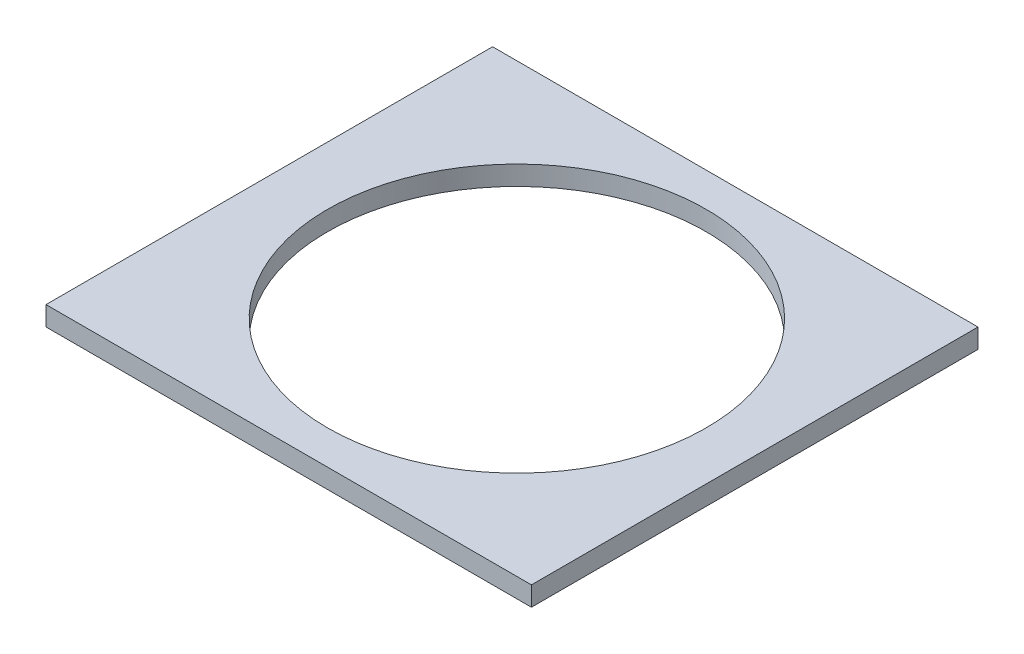
SolidWorks part; units mm, degrees
ref_plane "정면" through (0, 0, 0) normal (0, 0, 1) x (1, 0, 0)
ref_plane "윗면" through (0, 0, 0) normal (0, 1, 0) x (1, 0, 0)
ref_plane "우측면" through (0, 0, 0) normal (1, 0, 0) x (0, 0, -1)
sketch "스케치1" plane through (0, 0, 0) normal (0, 1, 0) x (1, 0, 0)
  line L1 (12.5, -11.5) -> (-12.5, -11.5)
  line L2 (12.5, -11.5) -> (12.5, 11.5)
  line L3 (12.5, 11.5) -> (-12.5, 11.5)
  line L4 (-12.5, -11.5) -> (-12.5, 11.5)
  line L5 (12.5, -11.5) -> (-12.5, 11.5) construction
  line L6 (12.5, 11.5) -> (-12.5, -11.5) construction
  point P0 (0, 0)
  dimension "D1" = 25
  dimension "D2" = 23
extrude "보스-돌출1" add sketch "스케치1" along normal blind 12
sketch "스케치2" plane through (0, 0, 0) normal (0, 1, 0) x (1, 0, 0)
  line L0 (12.5, 11.5) -> (-12.5, 11.5) construction
  line L1 (-11.5, 10.5) -> (13.5, 10.5)
  line L2 (-11.5, 10.5) -> (-11.5, -10.5)
  line L3 (-11.5, -10.5) -> (13.5, -10.5)
  line L4 (13.5, 10.5) -> (13.5, -10.5)
  line L5 (-12.5, 11.5) -> (-12.5, -11.5) construction
  dimension "D1" = 1
  dimension "D2" = 21
  dimension "D3" = 25
  dimension "D4" = 1
extrude "컷-돌출1" cut sketch "스케치2" along normal blind 11 from offset 1
sketch "스케치6" plane through (0, 0, 0) normal (0, 1, 0) x (1, 0, 0)
  line L1 (12.5, -11.5) -> (-12.5, -11.5)
  line L2 (12.5, -11.5) -> (12.5, 11.5)
  line L3 (12.5, 11.5) -> (-12.5, 11.5)
  line L4 (-12.5, -11.5) -> (-12.5, 11.5)
  line L5 (12.5, -11.5) -> (-12.5, 11.5) construction
  line L6 (12.5, 11.5) -> (-12.5, -11.5) construction
  point P0 (0, 0)
extrude "보스-돌출3" add sketch "스케치6" along normal blind 1 from offset 12 separate body
sketch "스케치8" plane through (0, 0, 0) normal (0, 1, 0) x (1, 0, 0)
  line L0 (-12.5, 11.5) -> (-12.5, -11.5) construction
  line L2 (-12.5, -11.5) -> (12.5, -11.5) construction
  circle A0 centre (0.25, 0) radius 9.75
  dimension "D1" = 3
  dimension "D2" = 19.5
  dimension "D3" = 1.75
extrude "컷-돌출2" cut sketch "스케치8" against normal blind 1 from surface at 13 starting at face at (0, 13, 0)
sketch "스케치10" plane through (0, 0, 0) normal (0, -1, 0) x (1, 0, 0)
  line L4 (-12.5, 11.5) -> (-12.5, -11.5)
  line L5 (-12.5, -11.5) -> (12.5, -11.5)
  line L6 (12.5, -11.5) -> (12.5, 11.5)
  line L7 (12.5, 11.5) -> (-12.5, 11.5)
  line L8 (-12.5, 11.5) -> (-12.5, -11.5)
  line L9 (-12.5, -11.5) -> (12.5, -11.5)
  line L10 (12.5, -11.5) -> (12.5, 11.5)
  line L11 (12.5, 11.5) -> (-12.5, 11.5)
  dimension "D1" = 0
extrude "컷-돌출4" cut sketch "스케치10" against normal blind 12
